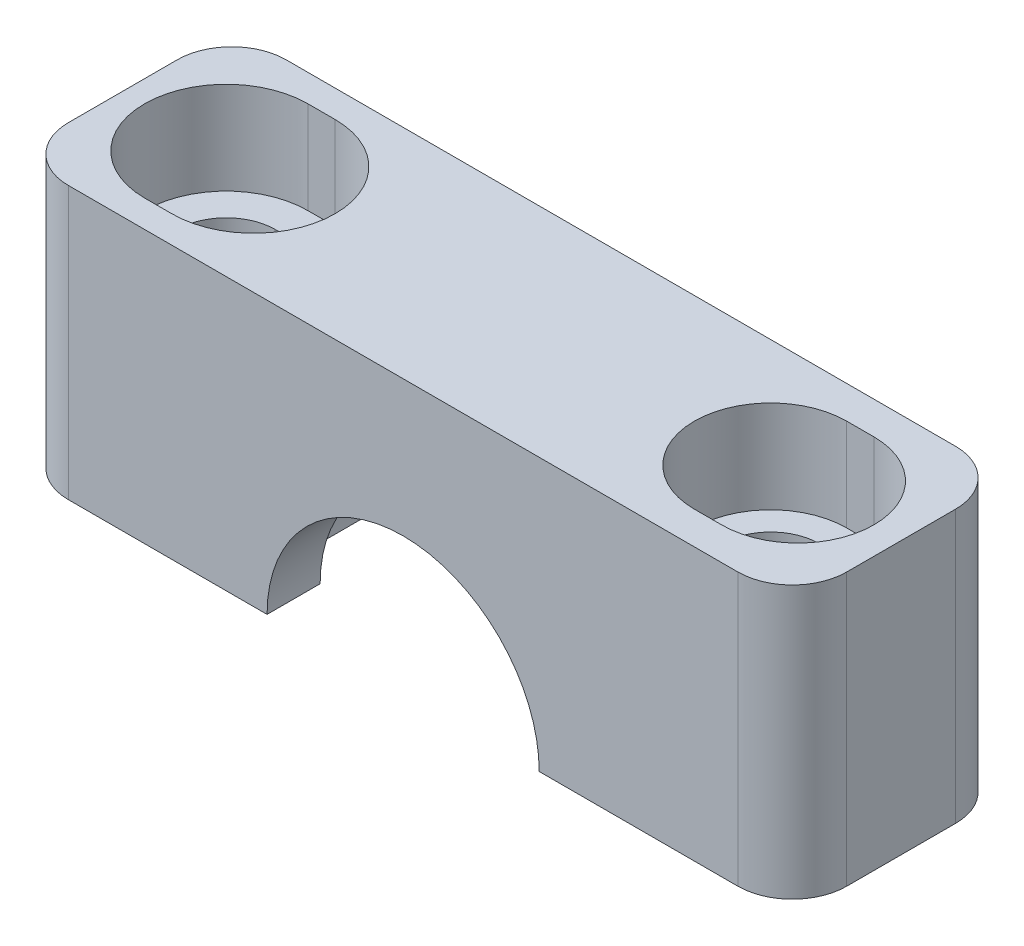
SolidWorks part; units mm, degrees
ref_plane "Front Plane" through (0, 0, 0) normal (0, 0, 1) x (1, 0, 0)
ref_plane "Top Plane" through (0, 0, 0) normal (0, 1, 0) x (1, 0, 0)
ref_plane "Right Plane" through (0, 0, 0) normal (1, 0, 0) x (0, 0, -1)
sketch "Sketch1" plane through (0, 0, 0) normal (0, 1, 0) x (1, 0, 0)
  line L1 (-15.621, -5.08) -> (15.621, -5.08)
  line L2 (-18.161, -2.54) -> (-18.161, 2.54)
  line L3 (-15.621, 5.08) -> (15.621, 5.08)
  line L4 (18.161, -2.54) -> (18.161, 2.54)
  line L5 (-18.161, -5.08) -> (18.161, 5.08) construction
  line L6 (-18.161, 5.08) -> (18.161, -5.08) construction
  arc A0 (-18.161, 2.54) -> (-15.621, 5.08) centre (-15.621, 2.54) cw
  arc A1 (-15.621, -5.08) -> (-18.161, -2.54) centre (-15.621, -2.54) cw
  arc A2 (15.621, 5.08) -> (18.161, 2.54) centre (15.621, 2.54) cw
  arc A3 (15.621, -5.08) -> (18.161, -2.54) centre (15.621, -2.54) ccw
  point P0 (0, 0)
  dimension "D3" = 2.54
  dimension "D1" = 36.322
  dimension "D2" = 10.16
extrude "Boss-Extrude1" add sketch "Sketch1" along normal blind 12.7
sketch "Sketch2" plane through (0, 0, 5.08) normal (0, 0, 1) x (1, 0, 0)
  line L0 (-15.621, 0) -> (15.621, 0) construction
  line L1 (-6.35, 0) -> (6.35, 0)
  arc A0 (-6.35, 0) -> (6.35, 0) centre (0, 0) cw
  dimension "D1" = 6.35
extrude "Cut-Extrude1" cut sketch "Sketch2" against normal through all
sketch "Sketch3" plane through (0, 0, 0) normal (0, 0, 1) x (1, 0, 0)
  line L0 (-8.001, 0) -> (8.001, 0)
  line L1 (6.35, 0) -> (15.621, 0) construction
  arc A0 (-8.001, 0) -> (8.001, 0) centre (0, 0) cw
  dimension "D1" = 8.001
extrude "Cut-Extrude2" cut sketch "Sketch3" against normal mid plane 5.207
sketch "Sketch4" plane through (0, 0, 0) normal (0, -1, 0) x (1, 0, 0)
  line L0 (12.065, 0) -> (13.335, 0) construction
  line L1 (12.065, 2.286) -> (13.335, 2.286)
  line L2 (12.065, -2.286) -> (13.335, -2.286)
  line L3 (-13.335, 0) -> (-12.065, 0) construction
  line L4 (-13.335, 2.286) -> (-12.065, 2.286)
  line L5 (-13.335, -2.286) -> (-12.065, -2.286)
  line L6 (-12.7, 0) -> (12.7, 0) construction
  line L7 (-12.065, -2.286) -> (12.065, -2.286) construction
  arc A0 (12.065, 2.286) -> (12.065, -2.286) centre (12.065, 0) ccw
  arc A1 (13.335, -2.286) -> (13.335, 2.286) centre (13.335, 0) ccw
  arc A2 (-13.335, 2.286) -> (-13.335, -2.286) centre (-13.335, 0) ccw
  arc A3 (-12.065, -2.286) -> (-12.065, 2.286) centre (-12.065, 0) ccw
  point P2 (12.7, 0)
  point P10 (-12.7, 0)
  point P17 (0, 0)
  dimension "D1" = 24.13
  dimension "D2" = 26.67
  dimension "D3" = 4.572
extrude "Cut-Extrude3" cut sketch "Sketch4" against normal through all
sketch "Sketch5" plane through (0, 12.7, 0) normal (0, 1, 0) x (1, 0, 0)
  line L4 (-12.065, 3.81) -> (-13.335, 3.81)
  line L5 (-13.335, -3.81) -> (-12.065, -3.81)
  line L6 (-12.065, 3.81) -> (-13.335, 3.81)
  line L7 (-13.335, -3.81) -> (-12.065, -3.81)
  line L10 (12.065, -3.556) -> (13.335, -3.556)
  line L11 (13.335, 3.556) -> (12.065, 3.556)
  line L12 (12.065, -3.556) -> (13.335, -3.556)
  line L13 (13.335, 3.556) -> (12.065, 3.556)
  arc A4 (-13.335, 3.81) -> (-13.335, -3.81) centre (-13.335, 0) ccw
  arc A5 (-12.065, -3.81) -> (-12.065, 3.81) centre (-12.065, 0) ccw
  arc A6 (-13.335, 3.81) -> (-13.335, -3.81) centre (-13.335, 0) ccw
  arc A7 (-12.065, -3.81) -> (-12.065, 3.81) centre (-12.065, 0) ccw
  arc A10 (13.335, -3.556) -> (13.335, 3.556) centre (13.335, 0) ccw
  arc A11 (12.065, 3.556) -> (12.065, -3.556) centre (12.065, 0) ccw
  arc A12 (13.335, -3.556) -> (13.335, 3.556) centre (13.335, 0) ccw
  arc A13 (12.065, 3.556) -> (12.065, -3.556) centre (12.065, 0) ccw
  dimension "D1" = 1.524
  dimension "D2" = 1.27
extrude "Cut-Extrude4" cut sketch "Sketch5" against normal blind 4.318
